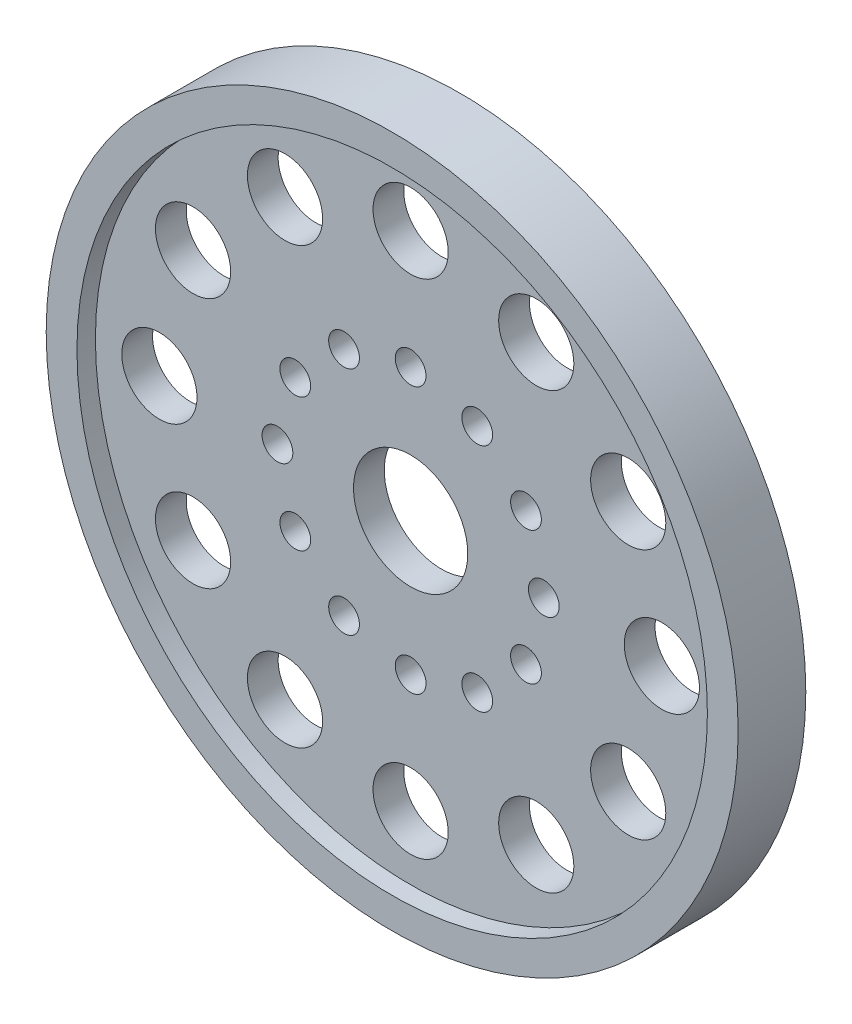
SolidWorks part; units mm, degrees
material "ABS"
ref_plane "Front Plane" through (0, 0, 0) normal (0, 0, 1) x (1, 0, 0)
ref_plane "Top Plane" through (0, 0, 0) normal (0, 1, 0) x (1, 0, 0)
ref_plane "Right Plane" through (0, 0, 0) normal (1, 0, 0) x (0, 0, -1)
sketch "Sketch1" plane through (0, 0, 0) normal (0, 0, 1) x (1, 0, 0)
  circle A0 centre (0, 0) radius 28.575
  dimension "D1" = 57.15
extrude "Boss-Extrude1" add sketch "Sketch1" along normal mid plane 5.588
sketch "Sketch2" plane through (0, 0, 2.794) normal (0, 0, 1) x (1, 0, 0)
  circle A0 centre (0, 0) radius 4.718
  circle A1 centre (0, 0) radius 11 construction
  circle A2 centre (0, 11) radius 1.27
  circle A3 centre (5.5001, 9.5268) radius 1.27
  circle A4 centre (9.5268, 5.5009) radius 1.27
  circle A5 centre (11.001, 0.001) radius 1.27
  circle A6 centre (9.5278, -5.4991) radius 1.27
  circle A7 centre (5.5019, -9.5258) radius 1.27
  circle A8 centre (0.002, -11) radius 1.27
  circle A9 centre (-5.4981, -9.5268) radius 1.27
  circle A10 centre (-9.5248, -5.5009) radius 1.27
  circle A11 centre (-10.999, -0.001) radius 1.27
  circle A12 centre (-9.5258, 5.4991) radius 1.27
  circle A13 centre (-5.4999, 9.5258) radius 1.27
  dimension "D1" = 9.4361
  dimension "D2" = 22
  dimension "D3" = 2.54
  dimension "D4" = 12
extrude "Cut-Extrude1" cut sketch "Sketch2" against normal through all
sketch "Sketch3" plane through (0, 0, 0) normal (0, 0, 1) x (1, 0, 0)
  circle A0 centre (0, 0) radius 26.035
  dimension "D1" = 52.07
extrude "Cut-Extrude2" cut sketch "Sketch3" against normal blind 1.651 from offset 1.27
mirror "Mirror1" about plane through (0, 0, 0) normal (0, 0, 1) of "Cut-Extrude2"
sketch "Sketch4" plane through (0, 0, 0) normal (0, 0, 1) x (1, 0, 0)
  circle A0 centre (0, 0) radius 20.75 construction
  circle A1 centre (0, 20.75) radius 3.1051
  circle A2 centre (10.375, 17.97) radius 3.1051
  circle A3 centre (17.97, 10.375) radius 3.1052
  circle A4 centre (20.75, 0) radius 3.1051
  circle A5 centre (17.97, -10.375) radius 3.1052
  circle A6 centre (10.375, -17.97) radius 3.1051
  circle A7 centre (0, -20.75) radius 3.1051
  circle A8 centre (-10.375, -17.97) radius 3.1051
  circle A9 centre (-17.97, -10.375) radius 3.1052
  circle A10 centre (-20.75, 0) radius 3.1051
  circle A11 centre (-17.97, 10.375) radius 3.1052
  circle A12 centre (-10.375, 17.97) radius 3.1051
  dimension "D1" = 41.5
  dimension "D2" = 6.2103
  dimension "D3" = 12
extrude "Cut-Extrude3" cut sketch "Sketch4" against normal through all and the other way through all
